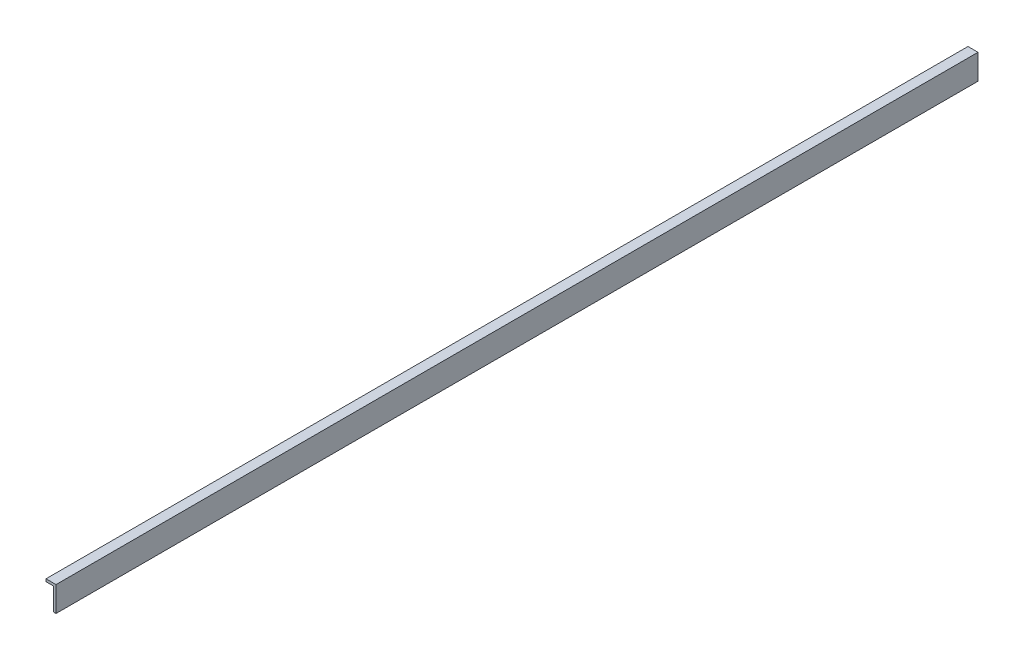
SolidWorks part; units mm, degrees
ref_plane "Front Plane" through (0, 0, 0) normal (0, 0, 1) x (1, 0, 0)
ref_plane "Top Plane" through (0, 0, 0) normal (0, 1, 0) x (1, 0, 0)
ref_plane "Right Plane" through (0, 0, 0) normal (1, 0, 0) x (0, 0, -1)
other "Configuration Table"
sketch "Sketch1" plane through (0, 0, 0) normal (0, 0, 1) x (1, 0, 0)
  line L0 (353.5, 404.5) -> (355.5, 404.5)
  line L1 (355.5, 404.5) -> (355.5, 424.5)
  line L2 (355.5, 424.5) -> (347.5, 424.5)
  line L3 (347.5, 424.5) -> (347.5, 422.5)
  line L4 (347.5, 422.5) -> (353.5, 422.5)
  line L5 (353.5, 422.5) -> (353.5, 404.5)
extrude "STORE_kaset_L_raf_2_sag_1" add sketch "Sketch1" against normal blind 735.5 from offset 20 separate body
